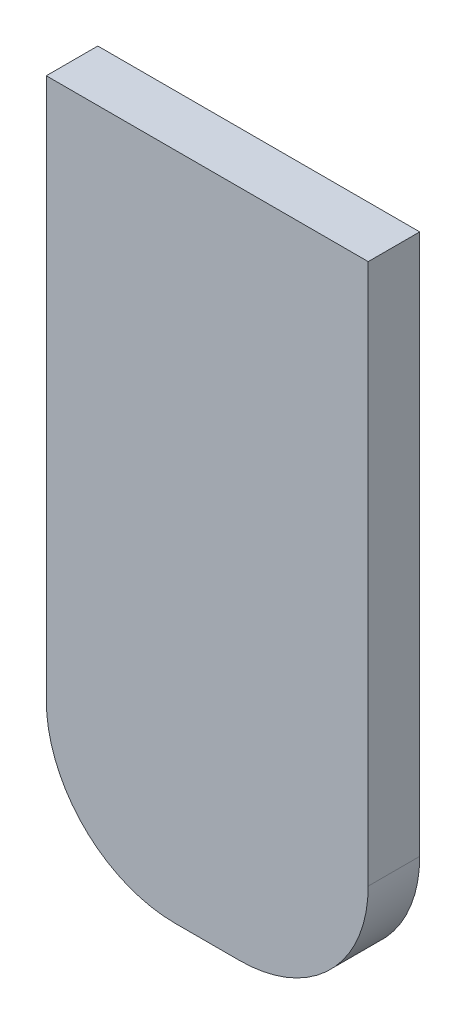
SolidWorks part; units mm, degrees
ref_plane "Front Plane" through (0, 0, 0) normal (0, 0, 1) x (1, 0, 0)
ref_plane "Top Plane" through (0, 0, 0) normal (0, 1, 0) x (1, 0, 0)
ref_plane "Right Plane" through (0, 0, 0) normal (1, 0, 0) x (0, 0, -1)
sketch "Sketch1" plane through (0, 0, 0) normal (0, 0, 1) x (1, 0, 0)
  line L1 (0, 0) -> (31.75, 0)
  line L2 (0, 0) -> (0, 66.04)
  line L3 (0, 66.04) -> (31.75, 66.04)
  line L4 (31.75, 0) -> (31.75, 66.04)
  dimension "D1" = 31.75
  dimension "D2" = 66.04
extrude "Boss-Extrude1" add sketch "Sketch1" along normal blind 5.08
fillet "Fillet1" radius 12.7 2 edges at (0, 0, 2.54) (31.75, 0, 2.54)
equation "\"MDF\"= .2"
equation "\"Foamcore\"= .1"
equation "\"GMaterial\"= \"MDF\""
equation "\"CutDistance\" = .1"
equation "\"D1@Boss-Extrude1\"=\"GMaterial\""
